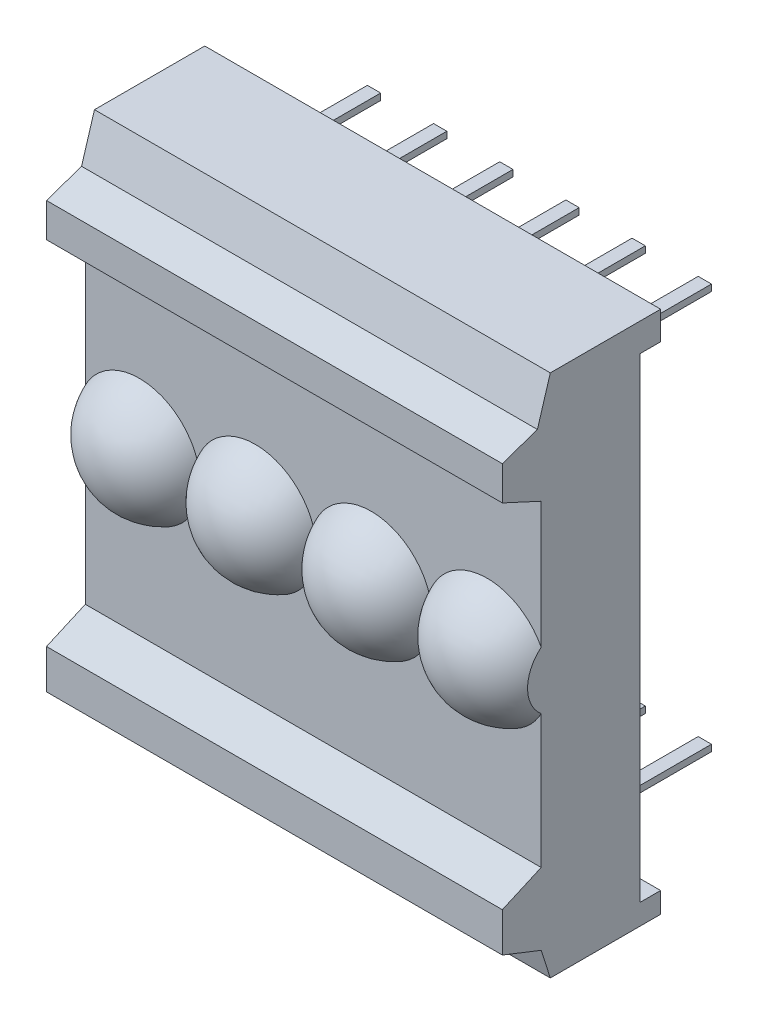
SolidWorks part; units mm, degrees
ref_plane "Front" through (0, 0, 0) normal (0, 0, 1) x (1, 0, 0)
ref_plane "Top" through (0, 0, 0) normal (0, 1, 0) x (1, 0, 0)
ref_plane "Right" through (0, 0, 0) normal (1, 0, 0) x (0, 0, -1)
sketch "草图1" plane through (0, 0, 0) normal (0, 0, 1) x (1, 0, 0)
  line L0 (0, 0) -> (17.5, 0)
  line L1 (17.5, 0) -> (17.5, 20.1)
  line L2 (17.5, 20.1) -> (0, 20.1)
  line L3 (0, 20.1) -> (0, 0)
  line L4 (0, 0) -> (0.1321, -0.1209)
  line L5 (0, 10.05) -> (17.5, 10.05) construction
  line L6 (2.075, 12.1986) -> (2.075, 7.9561) construction
  line L7 (6.525, 12.1723) -> (6.525, 7.9824) construction
  line L8 (10.975, 12.1723) -> (10.975, 7.9824) construction
  line L9 (15.425, 12.1723) -> (15.425, 7.9824) construction
  line L10 (2.075, 12.1723) -> (6.525, 12.1723) construction
  line L11 (6.525, 7.9824) -> (10.975, 7.9824) construction
  line L12 (6.525, 12.1723) -> (10.975, 12.1723) construction
  line L13 (8.75, 7.9824) -> (8.75, 12.1723) construction
  line L14 (17.5, 16.0079) -> (0, 16.0079)
  line L15 (17.5, 16.695) -> (0, 16.695)
  line L16 (17.5, 18.0006) -> (0, 18.0006)
  line L17 (17.5, 18.516) -> (0, 18.516)
  line L18 (17.5, 1.584) -> (0, 1.584)
  line L19 (17.5, 2.0994) -> (0, 2.0994)
  line L20 (17.5, 3.405) -> (0, 3.405)
  line L21 (17.5, 4.0921) -> (0, 4.0921)
  line L22 (60.2254, 20.1) -> (64.46, 20.1)
  line L23 (64.46, 20.1) -> (64.46, 19.0155)
  line L24 (64.46, 19.0155) -> (63.6679, 19.0155)
  line L25 (63.6679, 19.0155) -> (63.6679, 1.1328)
  line L26 (63.6679, 1.1328) -> (64.46, 1.1328)
  line L27 (64.46, 1.1328) -> (64.46, 0.3407)
  line L28 (64.46, 0.3407) -> (63.6679, 0.3407)
  line L29 (63.6679, 0.3407) -> (60.2254, 0.3407)
  line L30 (60.2254, 0.3407) -> (59.8751, 1.4365)
  line L31 (59.8751, 1.4365) -> (58.3848, 2.0235)
  line L32 (58.3848, 2.0235) -> (58.3848, 3.532)
  line L33 (58.3848, 3.532) -> (59.8751, 4.1908)
  line L34 (59.8751, 4.1908) -> (59.8751, 16.0079)
  line L35 (59.8751, 16.0079) -> (58.3848, 16.695)
  line L36 (58.3848, 16.695) -> (58.3848, 18.0006)
  line L37 (58.3848, 18.0006) -> (59.7303, 18.4659)
  line L38 (59.7303, 18.4659) -> (60.2254, 20.1)
  line L39 (67.6337, 7.6878) -> (67.6337, 12.3613)
  circle A0 centre (68.5373, 10.0245) radius 2.5054
  arc A1 (4.3, 11.3025) -> (0, 11.5423) centre (2.075, 10.0774) ccw
  arc A2 (4.3, 8.8522) -> (8.75, 8.8522) centre (6.525, 10.0774) ccw
  arc A3 (8.75, 8.8522) -> (13.2, 8.8522) centre (10.975, 10.0774) ccw
  arc A4 (13.2, 8.8522) -> (17.5, 8.6124) centre (15.425, 10.0774) ccw
  arc A5 (8.75, 11.3025) -> (4.3, 11.3025) centre (6.525, 10.0774) ccw
  arc A6 (13.2, 11.3025) -> (8.75, 11.3025) centre (10.975, 10.0774) ccw
  arc A7 (0, 8.6124) -> (4.3, 8.8522) centre (2.075, 10.0774) ccw
  arc A8 (17.5, 11.5423) -> (13.2, 11.3025) centre (15.425, 10.0774) ccw
  dimension "D6" = 5.08
  dimension "D7" = 5.0108
  dimension "D8" = 1.4903
  dimension "D9" = 5.08
  dimension "D1" = 17.5
  dimension "D2" = 20.1
  dimension "D4" = 4.45
  dimension "D5" = 8.75
  dimension "D10" = 0.9036
  dimension "D3" = 4
sketch "草图2" plane through (0, 0, 0) normal (1, 0, 0) x (0, 0, -1)
  line L0 (-3.4425, 20.1189) -> (0.7921, 20.1189)
  line L1 (0.7921, 20.1189) -> (0.7921, 19.0345)
  line L2 (0.7921, 19.0345) -> (0, 19.0345)
  line L3 (0, 19.0345) -> (0, 0.7921)
  line L4 (0, 0.7921) -> (0.7921, 0.7921)
  line L5 (0.7921, 0.7921) -> (0.7921, 0)
  line L6 (0.7921, 0) -> (0, 0)
  line L7 (0, 0) -> (-3.4425, 0)
  line L8 (-3.4425, 0) -> (-3.7929, 1.0958)
  line L9 (-3.7929, 1.0958) -> (-5.2831, 1.6829)
  line L10 (-5.2831, 1.6829) -> (-5.2831, 3.1913)
  line L11 (-5.2831, 3.1913) -> (-3.7929, 3.8502)
  line L12 (-3.7929, 3.8502) -> (-3.7929, 16.0268)
  line L13 (-3.7929, 16.0268) -> (-5.2831, 16.714)
  line L14 (-5.2831, 16.714) -> (-5.2831, 18.0195)
  line L15 (-5.2831, 18.0195) -> (-3.9377, 18.4848)
  line L16 (-3.9377, 18.4848) -> (-3.4425, 20.1189)
  dimension "D1" = 1.4903
extrude "凸台-拉伸1" add sketch "草图2" along normal blind 17.5
sketch3d "3D草图4" plane through (0, 0, 0) normal (0, 0, 1) x (1, 0, 0)
  dimension "D1" = 0.9
ref_plane "基准面1" through (0, 0, 2.8929) normal (0, 0, 1) x (1, 0, 0)
sketch "草图5" plane through (0, 0, 2.8929) normal (0, 0, 1) x (1, 0, 0)
  line L0 (0, 0.0189) -> (17.5, 0.0189)
  line L1 (17.5, 0.0189) -> (17.5, 4.111)
  line L2 (17.5, 20.1189) -> (0, 20.1189)
  line L3 (0, 20.1189) -> (0, 16.0268)
  line L4 (0, 0.0189) -> (0.1321, -0.102)
  line L5 (0, 10.0689) -> (17.5, 10.0689)
  line L6 (2.075, 12.2175) -> (2.075, 7.9751) construction
  line L7 (6.525, 12.1912) -> (6.525, 8.0014) construction
  line L8 (10.975, 12.1912) -> (10.975, 8.0014) construction
  line L9 (15.425, 12.1912) -> (15.425, 8.0014) construction
  line L10 (2.075, 12.1912) -> (6.525, 12.1912) construction
  line L11 (6.525, 8.0014) -> (10.975, 8.0014) construction
  line L12 (6.525, 12.1912) -> (10.975, 12.1912) construction
  line L13 (8.75, 8.0014) -> (8.75, 8.9564) construction
  line L14 (17.5, 16.0268) -> (0, 16.0268)
  line L15 (17.5, 16.714) -> (0, 16.714)
  line L16 (17.5, 18.0195) -> (0, 18.0195)
  line L17 (17.5, 18.5349) -> (0, 18.5349)
  line L18 (17.5, 1.603) -> (0, 1.603)
  line L19 (17.5, 2.1183) -> (0, 2.1183)
  line L20 (17.5, 3.4239) -> (0, 3.4239)
  line L21 (17.5, 4.111) -> (0, 4.111)
  line L22 (8.75, 11.2362) -> (8.75, 12.1912) construction
  line L23 (17.5, 16.0268) -> (17.5, 20.1189)
  line L24 (17.5, 10.0689) -> (17.5, 11.4907)
  line L25 (0, 11.4633) -> (0, 10.0689)
  line L26 (0, 4.111) -> (0, 0.0189)
  arc A0 (4.293, 11.2224) -> (0, 11.4633) centre (2.075, 10.0689) ccw
  arc A1 (8.75, 11.2362) -> (4.293, 11.2224) centre (6.525, 10.0963) ccw
  arc A2 (13.2, 11.2362) -> (8.75, 11.2362) centre (10.975, 10.0963) ccw
  arc A3 (17.5, 11.4907) -> (13.2, 11.2362) centre (15.425, 10.0963) ccw
  dimension "D2" = 5
  dimension "D4" = 5
  dimension "D5" = 5
  dimension "D1" = 8.75
revolve "旋转8" add sketch "草图5" angle 360 about L5
sketch "草图6" plane through (0, 0, 0) normal (0, 0, -1) x (-1, 0, 0)
  line L0 (0, 0.7921) -> (0, 19.0345) construction
  line L1 (-17.5, 17.7095) -> (0, 17.7095) construction
  line L2 (-17.5, 17.7095) -> (-17.5, 2.4095) construction
  line L3 (-17.5, 2.4095) -> (0, 2.4095) construction
  line L4 (0, 17.7095) -> (0, 2.4095) construction
  line L5 (-17.5, 20.1189) -> (-17.5, 0) construction
  line L6 (-17.5, 10.0595) -> (0, 10.0595) construction
  line L7 (-12.815, 17.5845) -> (-12.305, 17.5845)
  line L8 (-15.355, 17.5845) -> (-14.845, 17.5845)
  line L9 (-15.355, 17.5845) -> (-15.355, 17.8345)
  line L10 (-15.355, 17.8345) -> (-14.845, 17.8345)
  line L11 (-14.845, 17.5845) -> (-14.845, 17.8345)
  line L12 (-15.355, 17.5845) -> (-14.845, 17.8345) construction
  line L13 (-15.355, 17.8345) -> (-14.845, 17.5845) construction
  line L14 (-12.815, 17.5845) -> (-12.815, 17.8345)
  line L15 (-12.815, 17.8345) -> (-12.305, 17.8345)
  line L16 (-12.305, 17.5845) -> (-12.305, 17.8345)
  line L17 (-12.815, 17.5845) -> (-12.305, 17.8345) construction
  line L18 (-12.815, 17.8345) -> (-12.305, 17.5845) construction
  line L19 (-10.275, 17.5845) -> (-9.765, 17.5845)
  line L20 (-10.275, 17.5845) -> (-10.275, 17.8345)
  line L21 (-10.275, 17.8345) -> (-9.765, 17.8345)
  line L22 (-9.765, 17.5845) -> (-9.765, 17.8345)
  line L23 (-10.275, 17.5845) -> (-9.765, 17.8345) construction
  line L24 (-10.275, 17.8345) -> (-9.765, 17.5845) construction
  line L25 (-7.735, 17.5845) -> (-7.225, 17.5845)
  line L26 (-7.735, 17.5845) -> (-7.735, 17.8345)
  line L27 (-7.735, 17.8345) -> (-7.225, 17.8345)
  line L28 (-7.225, 17.5845) -> (-7.225, 17.8345)
  line L29 (-7.735, 17.5845) -> (-7.225, 17.8345) construction
  line L30 (-7.735, 17.8345) -> (-7.225, 17.5845) construction
  line L31 (-5.195, 17.5845) -> (-4.685, 17.5845)
  line L32 (-5.195, 17.5845) -> (-5.195, 17.8345)
  line L33 (-5.195, 17.8345) -> (-4.685, 17.8345)
  line L34 (-4.685, 17.5845) -> (-4.685, 17.8345)
  line L35 (-5.195, 17.5845) -> (-4.685, 17.8345) construction
  line L36 (-5.195, 17.8345) -> (-4.685, 17.5845) construction
  line L37 (-2.655, 17.5845) -> (-2.145, 17.5845)
  line L38 (-2.655, 17.5845) -> (-2.655, 17.8345)
  line L39 (-2.655, 17.8345) -> (-2.145, 17.8345)
  line L40 (-2.145, 17.5845) -> (-2.145, 17.8345)
  line L41 (-2.655, 17.5845) -> (-2.145, 17.8345) construction
  line L42 (-2.655, 17.8345) -> (-2.145, 17.5845) construction
  line L43 (-15.1, 17.7095) -> (-12.56, 17.7095) construction
  line L44 (-15.355, 2.2845) -> (-14.845, 2.2845)
  line L45 (-15.355, 2.2845) -> (-15.355, 2.5345)
  line L46 (-15.355, 2.5345) -> (-14.845, 2.5345)
  line L47 (-14.845, 2.2845) -> (-14.845, 2.5345)
  line L48 (-15.355, 2.2845) -> (-14.845, 2.5345) construction
  line L49 (-15.355, 2.5345) -> (-14.845, 2.2845) construction
  line L50 (-12.815, 2.2845) -> (-12.305, 2.2845)
  line L51 (-12.815, 2.2845) -> (-12.815, 2.5345)
  line L52 (-12.815, 2.5345) -> (-12.305, 2.5345)
  line L53 (-12.305, 2.2845) -> (-12.305, 2.5345)
  line L54 (-12.815, 2.2845) -> (-12.305, 2.5345) construction
  line L55 (-12.815, 2.5345) -> (-12.305, 2.2845) construction
  line L56 (-10.275, 2.2845) -> (-9.765, 2.2845)
  line L57 (-10.275, 2.2845) -> (-10.275, 2.5345)
  line L58 (-10.275, 2.5345) -> (-9.765, 2.5345)
  line L59 (-9.765, 2.2845) -> (-9.765, 2.5345)
  line L60 (-10.275, 2.2845) -> (-9.765, 2.5345) construction
  line L61 (-10.275, 2.5345) -> (-9.765, 2.2845) construction
  line L62 (-7.735, 2.2845) -> (-7.225, 2.2845)
  line L63 (-7.735, 2.2845) -> (-7.735, 2.5345)
  line L64 (-7.735, 2.5345) -> (-7.225, 2.5345)
  line L65 (-7.225, 2.2845) -> (-7.225, 2.5345)
  line L66 (-7.735, 2.2845) -> (-7.225, 2.5345) construction
  line L67 (-7.735, 2.5345) -> (-7.225, 2.2845) construction
  line L68 (-5.195, 2.2845) -> (-4.685, 2.2845)
  line L69 (-5.195, 2.2845) -> (-5.195, 2.5345)
  line L70 (-5.195, 2.5345) -> (-4.685, 2.5345)
  line L71 (-4.685, 2.2845) -> (-4.685, 2.5345)
  line L72 (-5.195, 2.2845) -> (-4.685, 2.5345) construction
  line L73 (-5.195, 2.5345) -> (-4.685, 2.2845) construction
  line L74 (-2.655, 2.2845) -> (-2.145, 2.2845)
  line L75 (-2.655, 2.2845) -> (-2.655, 2.5345)
  line L76 (-2.655, 2.5345) -> (-2.145, 2.5345)
  line L77 (-2.145, 2.2845) -> (-2.145, 2.5345)
  line L78 (-2.655, 2.2845) -> (-2.145, 2.5345) construction
  line L79 (-2.655, 2.5345) -> (-2.145, 2.2845) construction
  line L80 (-15.1, 2.4095) -> (-12.56, 2.4095) construction
  line L81 (-9.765, 2.5345) -> (-7.735, 2.5345) construction
  line L82 (-7.735, 2.2845) -> (-9.765, 2.2845) construction
  line L83 (-8.75, 2.2845) -> (-8.75, 2.5345) construction
  line L84 (-17.5, 0.7921) -> (0, 0.7921) construction
  point P13 (-15.1, 17.7095)
  point P18 (-15.1, 2.4095)
  point P20 (-12.56, 17.7095)
  point P25 (-10.02, 17.7095)
  point P30 (-7.48, 17.7095)
  point P35 (-4.94, 17.7095)
  point P40 (-2.4, 17.7095)
  point P51 (-12.56, 2.4095)
  point P56 (-10.02, 2.4095)
  point P61 (-7.48, 2.4095)
  point P66 (-4.94, 2.4095)
  point P71 (-2.4, 2.4095)
  point P81 (-8.75, 0.7921)
  dimension "D1" = 15.3
  dimension "D2" = 7.65
  dimension "D3" = 0.51
  dimension "D4" = 0.25
  dimension "D6" = 2.54
  dimension "D8" = 2.54
  dimension "D9" = 0
  dimension "D5" = 6
  dimension "D7" = 6
extrude "凸台-拉伸2" add sketch "草图6" along normal blind 4.89
